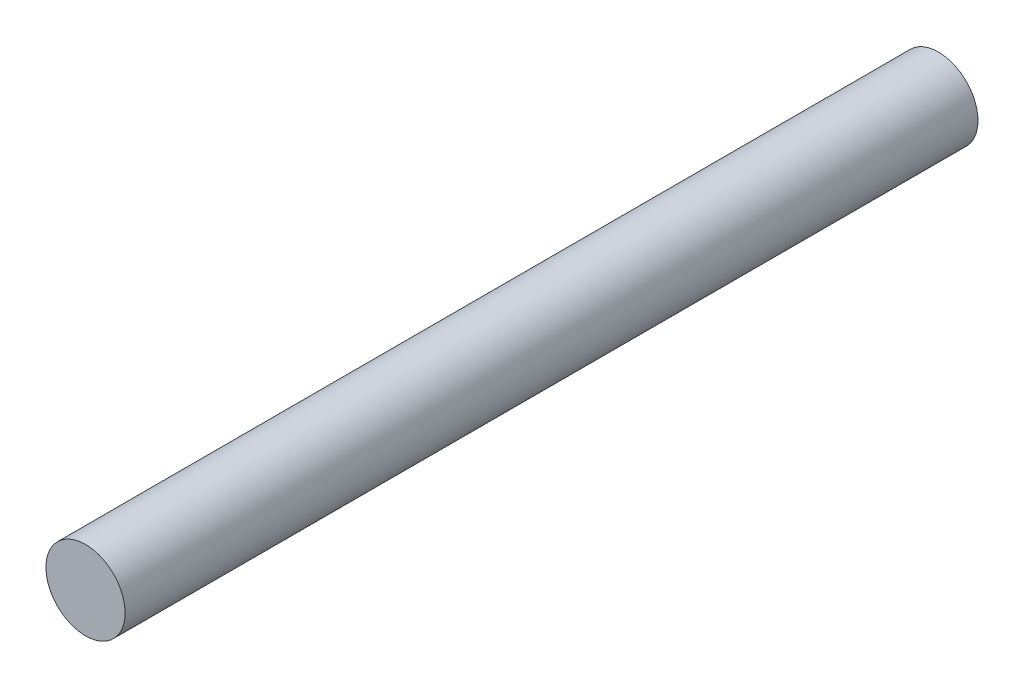
SolidWorks part; units mm, degrees
material "201 Annealed Stainless Steel (SS)"
ref_plane "Front Plane" through (0, 0, 0) normal (0, 0, 1) x (1, 0, 0)
ref_plane "Top Plane" through (0, 0, 0) normal (0, 1, 0) x (1, 0, 0)
ref_plane "Right Plane" through (0, 0, 0) normal (1, 0, 0) x (0, 0, -1)
sketch "Sketch1" plane through (0, 0, 0) normal (0, 0, 1) x (1, 0, 0)
  circle A0 centre (0, 0) radius 3.25
  dimension "D1" = 6.5
extrude "Boss-Extrude1" add sketch "Sketch1" along normal blind 70
